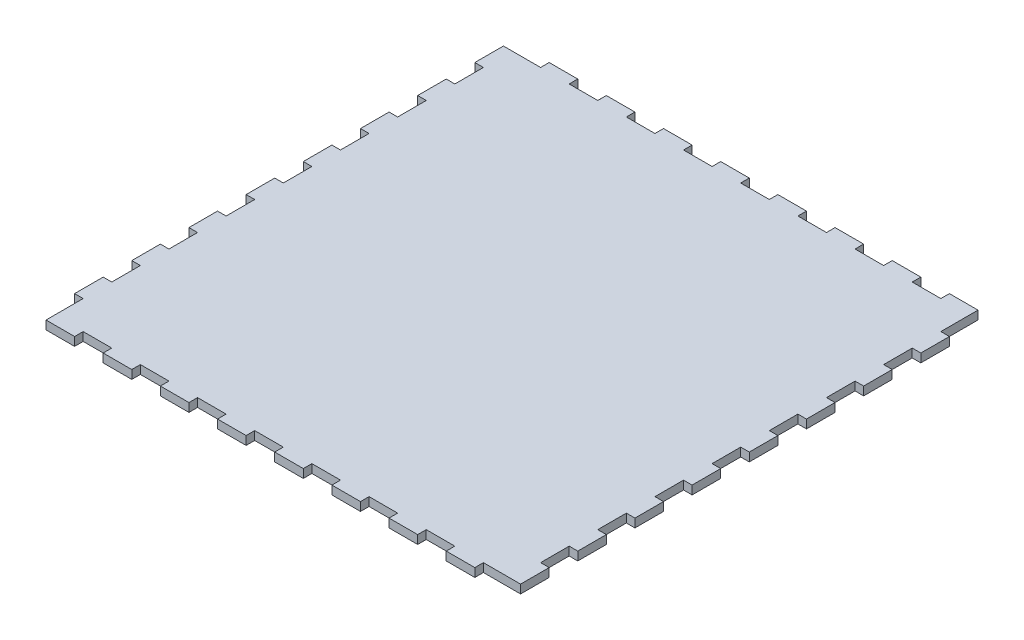
SolidWorks part; units mm, degrees
ref_plane "Front Plane" through (0, 0, 0) normal (0, 0, 1) x (1, 0, 0)
ref_plane "Top Plane" through (0, 0, 0) normal (0, 1, 0) x (1, 0, 0)
ref_plane "Right Plane" through (0, 0, 0) normal (1, 0, 0) x (0, 0, -1)
sketch "Sketch1" plane through (0, 0, 0) normal (0, 1, 0) x (1, 0, 0)
  line L0 (80, 80) -> (80, 70)
  line L1 (83, 70) -> (83, 60)
  line L2 (83, 60) -> (80, 60)
  line L3 (80, 70) -> (83, 70)
  line L4 (80, 60) -> (80, 50)
  line L5 (80, 50) -> (83, 50)
  line L6 (83, 50) -> (83, 40)
  line L7 (83, 40) -> (80, 40)
  line L8 (80, 40) -> (80, 30)
  line L9 (80, 30) -> (83, 30)
  line L10 (83, 30) -> (83, 20)
  line L11 (83, 20) -> (80, 20)
  line L12 (80, 20) -> (80, 10)
  line L13 (80, 10) -> (83, 10)
  line L14 (83, 10) -> (83, 0)
  line L15 (83, 0) -> (80, 0)
  line L16 (80, 0) -> (80, -10)
  line L17 (80, -10) -> (83, -10)
  line L18 (83, -10) -> (83, -20)
  line L19 (83, -20) -> (80, -20)
  line L20 (80, -20) -> (80, -30)
  line L21 (80, -30) -> (83, -30)
  line L22 (83, -30) -> (83, -40)
  line L23 (83, -40) -> (80, -40)
  line L24 (80, -40) -> (80, -50)
  line L25 (80, -50) -> (83, -50)
  line L26 (83, -50) -> (83, -60)
  line L27 (83, -60) -> (80, -60)
  line L28 (80, -60) -> (80, -70)
  line L29 (80, -70) -> (83, -70)
  line L30 (83, -70) -> (83, -80)
  line L31 (83, -80) -> (80, -80)
  line L32 (80, 80) -> (80, -80) construction
  line L33 (-956.5342, 0) -> (49043.4658, 0) construction
  line L34 (80, -80) -> (70, -80)
  line L35 (70, -83) -> (60, -83)
  line L36 (60, -83) -> (60, -80)
  line L37 (70, -80) -> (70, -83)
  line L38 (60, -80) -> (50, -80)
  line L39 (50, -80) -> (50, -83)
  line L40 (50, -83) -> (40, -83)
  line L41 (40, -83) -> (40, -80)
  line L42 (40, -80) -> (30, -80)
  line L43 (30, -80) -> (30, -83)
  line L44 (30, -83) -> (20, -83)
  line L45 (20, -83) -> (20, -80)
  line L46 (20, -80) -> (10, -80)
  line L47 (10, -80) -> (10, -83)
  line L48 (10, -83) -> (0, -83)
  line L49 (0, -83) -> (0, -80)
  line L50 (0, -80) -> (-10, -80)
  line L51 (-10, -80) -> (-10, -83)
  line L52 (-10, -83) -> (-20, -83)
  line L53 (-20, -83) -> (-20, -80)
  line L54 (-20, -80) -> (-30, -80)
  line L55 (-30, -80) -> (-30, -83)
  line L56 (-30, -83) -> (-40, -83)
  line L57 (-40, -83) -> (-40, -80)
  line L58 (-40, -80) -> (-50, -80)
  line L59 (-50, -80) -> (-50, -83)
  line L60 (-50, -83) -> (-60, -83)
  line L61 (-60, -83) -> (-60, -80)
  line L62 (-60, -80) -> (-70, -80)
  line L63 (-70, -80) -> (-70, -83)
  line L64 (-70, -83) -> (-80, -83)
  line L65 (-80, -83) -> (-80, -80)
  line L66 (80, -80) -> (-80, -80) construction
  line L67 (-80, -80) -> (-80, -70)
  line L68 (-83, -70) -> (-83, -60)
  line L69 (-83, -60) -> (-80, -60)
  line L70 (-80, -70) -> (-83, -70)
  line L71 (-80, -60) -> (-80, -50)
  line L72 (-80, -50) -> (-83, -50)
  line L73 (-83, -50) -> (-83, -40)
  line L74 (-83, -40) -> (-80, -40)
  line L75 (-80, -40) -> (-80, -30)
  line L76 (-80, -30) -> (-83, -30)
  line L77 (-83, -30) -> (-83, -20)
  line L78 (-83, -20) -> (-80, -20)
  line L79 (-80, -20) -> (-80, -10)
  line L80 (-80, -10) -> (-83, -10)
  line L81 (-83, -10) -> (-83, 0)
  line L82 (-83, 0) -> (-80, 0)
  line L83 (-80, 0) -> (-80, 10)
  line L84 (-80, 10) -> (-83, 10)
  line L85 (-83, 10) -> (-83, 20)
  line L86 (-83, 20) -> (-80, 20)
  line L87 (-80, 20) -> (-80, 30)
  line L88 (-80, 30) -> (-83, 30)
  line L89 (-83, 30) -> (-83, 40)
  line L90 (-83, 40) -> (-80, 40)
  line L91 (-80, 40) -> (-80, 50)
  line L92 (-80, 50) -> (-83, 50)
  line L93 (-83, 50) -> (-83, 60)
  line L94 (-83, 60) -> (-80, 60)
  line L95 (-80, 60) -> (-80, 70)
  line L96 (-80, 70) -> (-83, 70)
  line L97 (-83, 70) -> (-83, 80)
  line L98 (-83, 80) -> (-80, 80)
  line L99 (-80, -80) -> (-80, 80) construction
  line L100 (-80, 80) -> (-70, 80)
  line L101 (-70, 83) -> (-60, 83)
  line L102 (-60, 83) -> (-60, 80)
  line L103 (-70, 80) -> (-70, 83)
  line L104 (-60, 80) -> (-50, 80)
  line L105 (-50, 80) -> (-50, 83)
  line L106 (-50, 83) -> (-40, 83)
  line L107 (-40, 83) -> (-40, 80)
  line L108 (-40, 80) -> (-30, 80)
  line L109 (-30, 80) -> (-30, 83)
  line L110 (-30, 83) -> (-20, 83)
  line L111 (-20, 83) -> (-20, 80)
  line L112 (-20, 80) -> (-10, 80)
  line L113 (-10, 80) -> (-10, 83)
  line L114 (-10, 83) -> (0, 83)
  line L115 (0, 83) -> (0, 80)
  line L116 (0, 80) -> (10, 80)
  line L117 (10, 80) -> (10, 83)
  line L118 (10, 83) -> (20, 83)
  line L119 (20, 83) -> (20, 80)
  line L120 (20, 80) -> (30, 80)
  line L121 (30, 80) -> (30, 83)
  line L122 (30, 83) -> (40, 83)
  line L123 (40, 83) -> (40, 80)
  line L124 (40, 80) -> (50, 80)
  line L125 (50, 80) -> (50, 83)
  line L126 (50, 83) -> (60, 83)
  line L127 (60, 83) -> (60, 80)
  line L128 (60, 80) -> (70, 80)
  line L129 (70, 80) -> (70, 83)
  line L130 (70, 83) -> (80, 83)
  line L131 (80, 83) -> (80, 80)
  line L132 (-80, 80) -> (80, 80) construction
  line L133 (0, -919.7936) -> (0, 49080.2064) construction
  dimension "D1" = 3
  dimension "D2" = 10
  dimension "D3" = 8
  dimension "D4" = 4
extrude "Boss-Extrude1" add sketch "Sketch1" along normal blind 3
